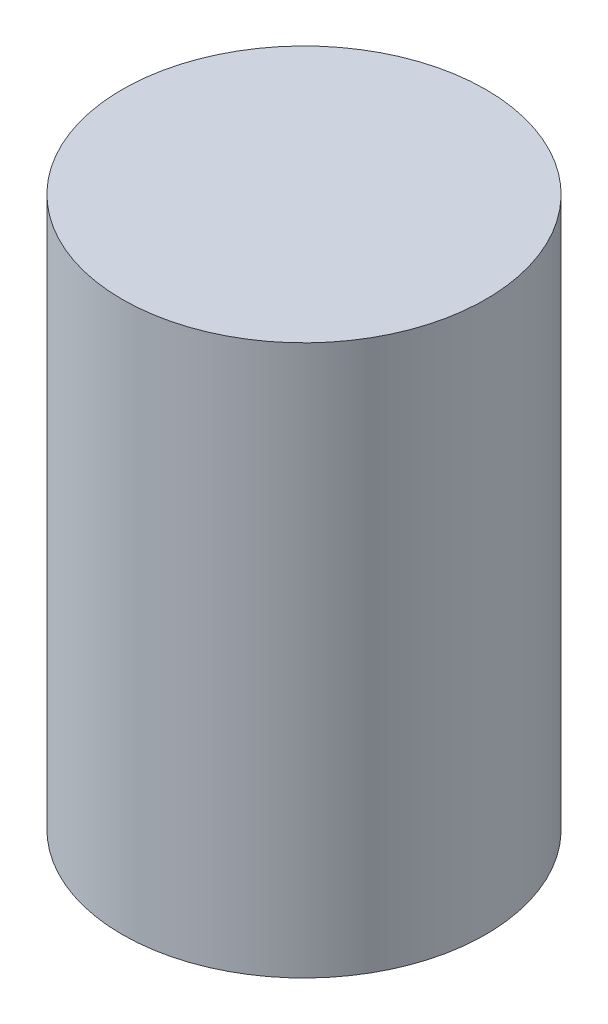
SolidWorks part; units mm, degrees
ref_plane "Front Plane" through (0, 0, 0) normal (1, 0, 0) x (0, 1, 0)
ref_plane "Top Plane" through (0, 0, 0) normal (0, 0, 1) x (0, 1, 0)
ref_plane "Right Plane" through (0, 0, 0) normal (0, 1, 0) x (-1, 0, 0)
sketch "Sketch2" plane through (0, 0, 0) normal (1, 0, 0) x (0, 1, 0)
  line L1 (-13.0076, 0) -> (19.1807, 0) construction
  line L3 (-7.5, 0) -> (15.1929, 0)
  line L7 (15.1929, 7.5) -> (15.1929, 0)
  line L8 (-7.5, 7.5) -> (-7.5, 0)
  line L9 (-7.5, 7.5) -> (15.1929, 7.5)
  dimension "D1" = 15
revolve "Revolve2" add sketch "Sketch2" angle 360 about L1
